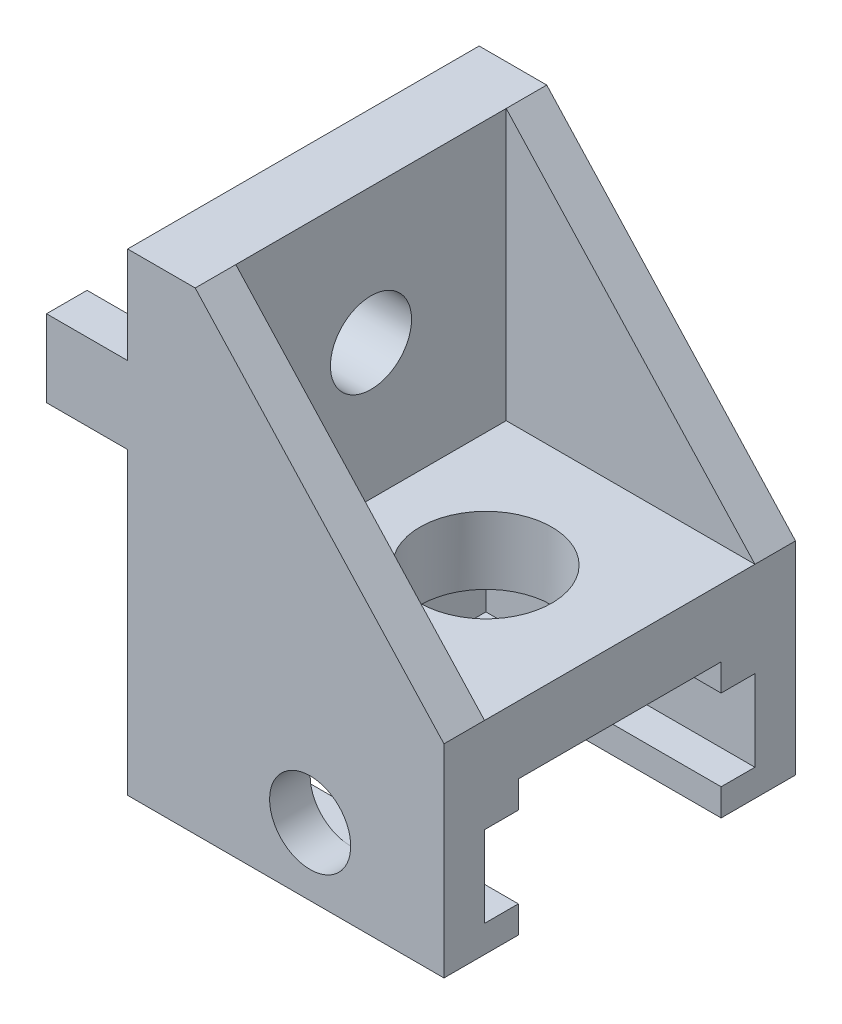
SolidWorks part; units mm, degrees
ref_plane "Front Plane" through (0, 0, 0) normal (0, 0, 1) x (1, 0, 0)
ref_plane "Top Plane" through (0, 0, 0) normal (0, 1, 0) x (1, 0, 0)
ref_plane "Right Plane" through (0, 0, 0) normal (1, 0, 0) x (0, 0, -1)
sketch "Sketch1" plane through (0, 0, 0) normal (0, 1, 0) x (1, 0, 0)
  line L1 (-13.5, 13) -> (13.5, 13)
  line L2 (-13.5, 13) -> (-13.5, -13)
  line L3 (-13.5, -13) -> (13.5, -13)
  line L4 (13.5, 13) -> (13.5, -13)
  line L5 (-13.5, 13) -> (13.5, -13) construction
  line L6 (-13.5, -13) -> (13.5, 13) construction
  point P0 (0, 0)
  dimension "D1" = 26
  dimension "D2" = 27
extrude "Boss-Extrude1" add sketch "Sketch1" along normal blind 15
sketch "Sketch4" plane through (13.5, 0, 0) normal (1, 0, 0) x (0, 0, -1)
  line L0 (-13, 15) -> (-13, 0) construction
  line L2 (-13, 7.5) -> (-13, 2.5)
  line L5 (-7.5, 2) -> (-7.5, 0)
  line L6 (-10, 8) -> (-7.5, 8)
  line L7 (-10, 8) -> (-10, 2)
  line L8 (-10, 2) -> (-7.5, 2)
  line L9 (10, 8) -> (10, 2)
  line L10 (-7.5, 10) -> (7.5, 10)
  line L11 (-7.5, 10) -> (-7.5, 8)
  line L12 (-7.5, 0) -> (7.5, 0)
  line L13 (7.5, 10) -> (7.5, 8)
  line L14 (7.5, 8) -> (10, 8)
  line L15 (7.5, 2) -> (10, 2)
  line L16 (7.5, 2) -> (7.5, 0)
  line M1 (-13, 0) -> (13, 0)
extrude "Cut-Extrude2" cut sketch "Sketch4" against normal blind 23.5 contours L16 L15 L9 L14 L13 L10 L11 L6 L7 L8 L5 M1
sketch "Sketch5" plane through (0, 0, -13) normal (0, 0, -1) x (-1, 0, 0)
  line L1 (-13.5, 15) -> (-9.8987, 15)
  line L2 (-13.5, 15) -> (-13.5, 0)
  line L3 (-13.5, 0) -> (-9.8987, 0)
  line L4 (-9.8987, 15) -> (-9.8987, 0)
extrude "Cut-Extrude3" cut sketch "Sketch5" against normal through all
sketch "Sketch6" plane through (0, 0, -13) normal (0, 0, -1) x (-1, 0, 0)
  circle A0 centre (0, 5) radius 3
  dimension "D1" = 6
extrude "Cut-Extrude4" cut sketch "Sketch6" against normal through all
sketch "Sketch7" plane through (0, 15, 0) normal (0, 1, 0) x (1, 0, 0)
  line L0 (9.8987, 13) -> (-13.5, 13) construction
  line L1 (-13.5, -13) -> (-8.5, -13)
  line L2 (-13.5, -13) -> (-13.5, 13)
  line L3 (-13.5, 13) -> (-8.5, 13)
  line L4 (-8.5, -13) -> (-8.5, 13)
  dimension "D1" = 5
extrude "Boss-Extrude2" add sketch "Sketch7" along normal blind 20
sketch "Sketch8" plane through (0, 0, -13) normal (0, 0, -1) x (-1, 0, 0)
  line L0 (8.5, 35) -> (-9.8987, 15)
  line L1 (-9.8987, 15) -> (8.5, 15)
  line L2 (8.5, 15) -> (8.5, 35)
  line L3 (13.5, 35) -> (13.5, 0) construction
  line L4 (13.5, 27.85) -> (19.5, 27.85)
  line L5 (13.5, 27.85) -> (13.5, 22.15)
  line L6 (13.5, 22.15) -> (19.5, 22.15)
  line L7 (19.5, 27.85) -> (19.5, 22.15)
  line L8 (19.5, 22.1) -> (19.5, 27.9) construction
extrude "Boss-Extrude3" add sketch "Sketch8" against normal blind 3
sketch "Sketch9" plane through (0, 0, 13) normal (0, 0, 1) x (1, 0, 0)
  line L0 (-8.5, 35) -> (9.8987, 15)
  line L1 (9.8987, 15) -> (-8.5, 15)
  line L2 (-8.5, 15) -> (-8.5, 35)
  line L7 (-19.5, 27.85) -> (-19.5, 22.15)
  line L8 (-19.5, 22.15) -> (-13.5, 22.15)
  line L9 (-13.5, 22.15) -> (-13.5, 27.85)
  line L10 (-13.5, 27.85) -> (-19.5, 27.85)
  line L11 (-19.5, 22.15) -> (-13.5, 22.15)
  line L12 (-13.5, 22.15) -> (-13.5, 27.85)
  line L13 (-13.5, 27.85) -> (-19.5, 27.85)
  line L14 (-19.5, 27.85) -> (-19.5, 22.15)
  dimension "D1" = 0
extrude "Boss-Extrude4" add sketch "Sketch9" against normal blind 3
sketch "Sketch10" plane through (-8.5, 0, 0) normal (1, 0, 0) x (0, 0, -1)
  line L0 (-13, 25) -> (13, 25) construction
  line L1 (13, 35) -> (13, 15) construction
  circle A0 centre (0, 25) radius 3
  dimension "D1" = 6
extrude "Cut-Extrude5" cut sketch "Sketch10" against normal through all
sketch "Sketch11" plane through (0, 15, 0) normal (0, 1, 0) x (1, 0, 0)
  circle A0 centre (0, 0) radius 4.875
  dimension "D1" = 9.75
extrude "Cut-Extrude6" cut sketch "Sketch11" against normal through all
